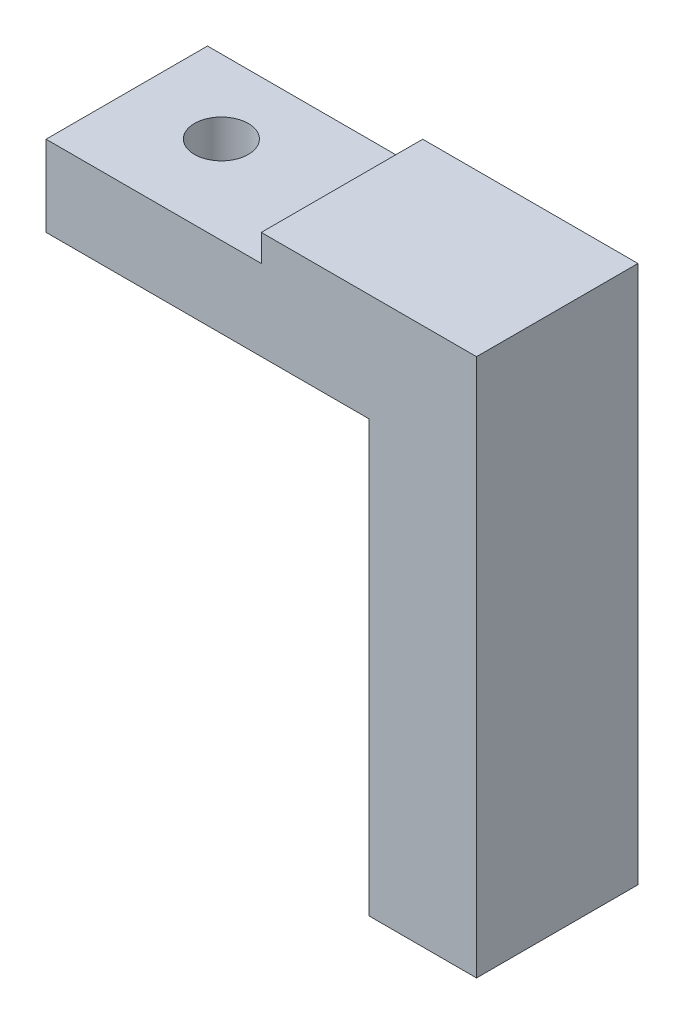
SolidWorks part; units mm, degrees
ref_plane "Front Plane" through (0, 0, 0) normal (0, 0, 1) x (1, 0, 0)
ref_plane "Top Plane" through (0, 0, 0) normal (0, 1, 0) x (1, 0, 0)
ref_plane "Right Plane" through (0, 0, 0) normal (1, 0, 0) x (0, 0, -1)
sketch "Sketch1" plane through (0, 0, 0) normal (0, 1, 0) x (1, 0, 0)
  line L1 (0, 0) -> (15, 0)
  line L2 (0, 0) -> (0, -6)
  line L3 (0, -6) -> (15, -6)
  line L4 (15, 0) -> (15, -6)
  dimension "D1" = 15
  dimension "D2" = 6
extrude "Boss-Extrude1" add sketch "Sketch1" along normal blind 3
sketch "Sketch2" plane through (0, 3, 0) normal (0, 1, 0) x (1, 0, 0)
  line L0 (0, 0) -> (0, -6) construction
  circle A0 centre (3.25, -2.7332) radius 1
  dimension "D2" = 2
  dimension "D1" = 3.25
extrude "Cut-Extrude1" cut sketch "Sketch2" against normal up to next
sketch "Sketch3" plane through (0, 0, 0) normal (0, -1, 0) x (1, 0, 0)
  line L0 (15, 0) -> (0, 0) construction
  line L1 (15, 6) -> (12, 6)
  line L2 (15, 6) -> (15, 0)
  line L3 (15, 0) -> (12, 0)
  line L4 (12, 6) -> (12, 0)
  dimension "D1" = 3
extrude "Boss-Extrude2" add sketch "Sketch3" along normal blind 16
sketch "Sketch4" plane through (15, 0, 0) normal (1, 0, 0) x (0, 0, -1)
  line L1 (-6, 3) -> (0, 3)
  line L2 (-6, 3) -> (-6, -16)
  line L3 (-6, -16) -> (0, -16)
  line L4 (0, 3) -> (0, -16)
extrude "Boss-Extrude3" add sketch "Sketch4" along normal blind 1
sketch "Sketch5" plane through (0, 3, 0) normal (0, 1, 0) x (1, 0, 0)
  line L0 (16, 0) -> (0, 0) construction
  line L1 (8, 0) -> (16, 0)
  line L2 (8, 0) -> (8, -6)
  line L3 (8, -6) -> (16, -6)
  line L4 (16, 0) -> (16, -6)
extrude "Boss-Extrude4" add sketch "Sketch5" along normal blind 1
